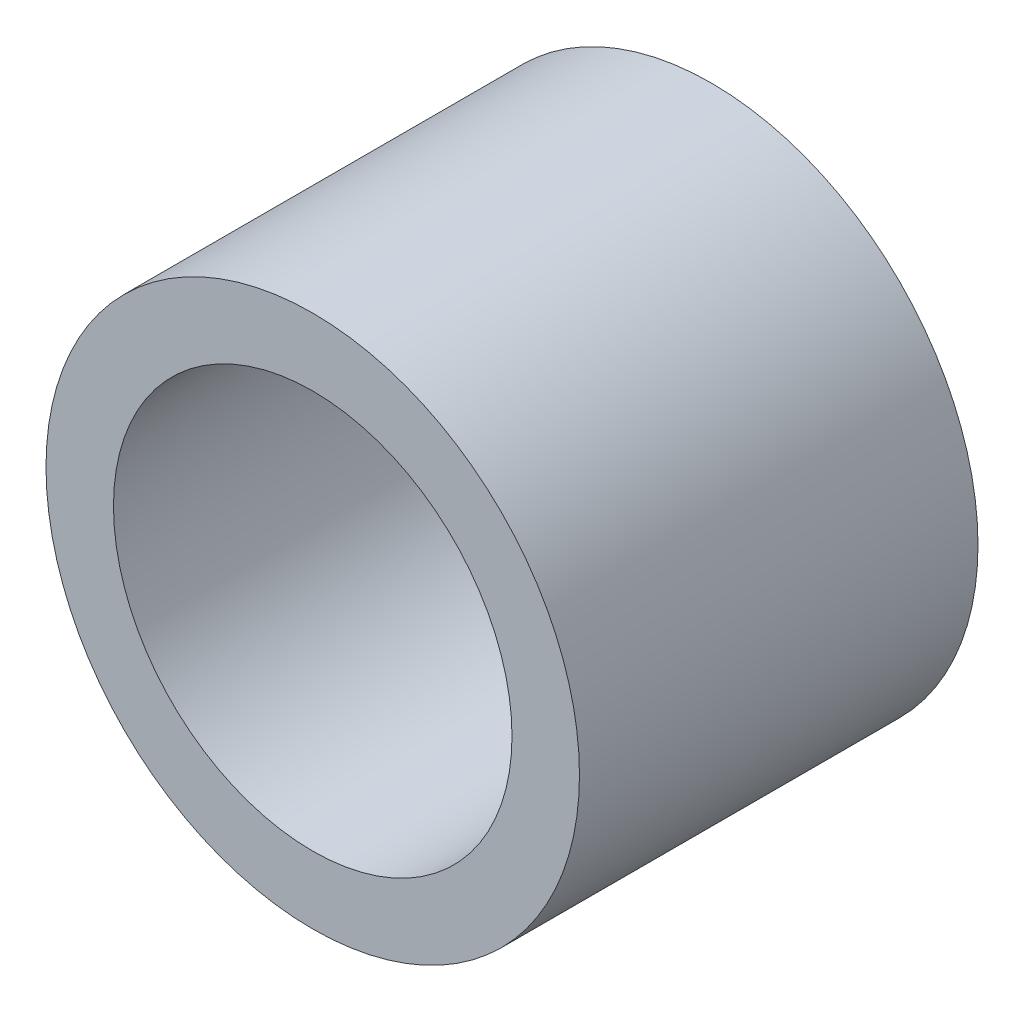
SolidWorks part; units mm, degrees
ref_plane "Front Plane" through (0, 0, 0) normal (0, 0, 1) x (1, 0, 0)
ref_plane "Top Plane" through (0, 0, 0) normal (0, 1, 0) x (1, 0, 0)
ref_plane "Right Plane" through (0, 0, 0) normal (1, 0, 0) x (0, 0, -1)
sketch "Sketch1" plane through (0, 0, 0) normal (0, 0, 1) x (1, 0, 0)
  circle A0 centre (0, 0) radius 6.35
  circle A1 centre (0, 0) radius 8.5
  dimension "D1" = 17
  dimension "D2" = 12.7
extrude "Boss-Extrude1" add sketch "Sketch1" along normal blind 12.7
